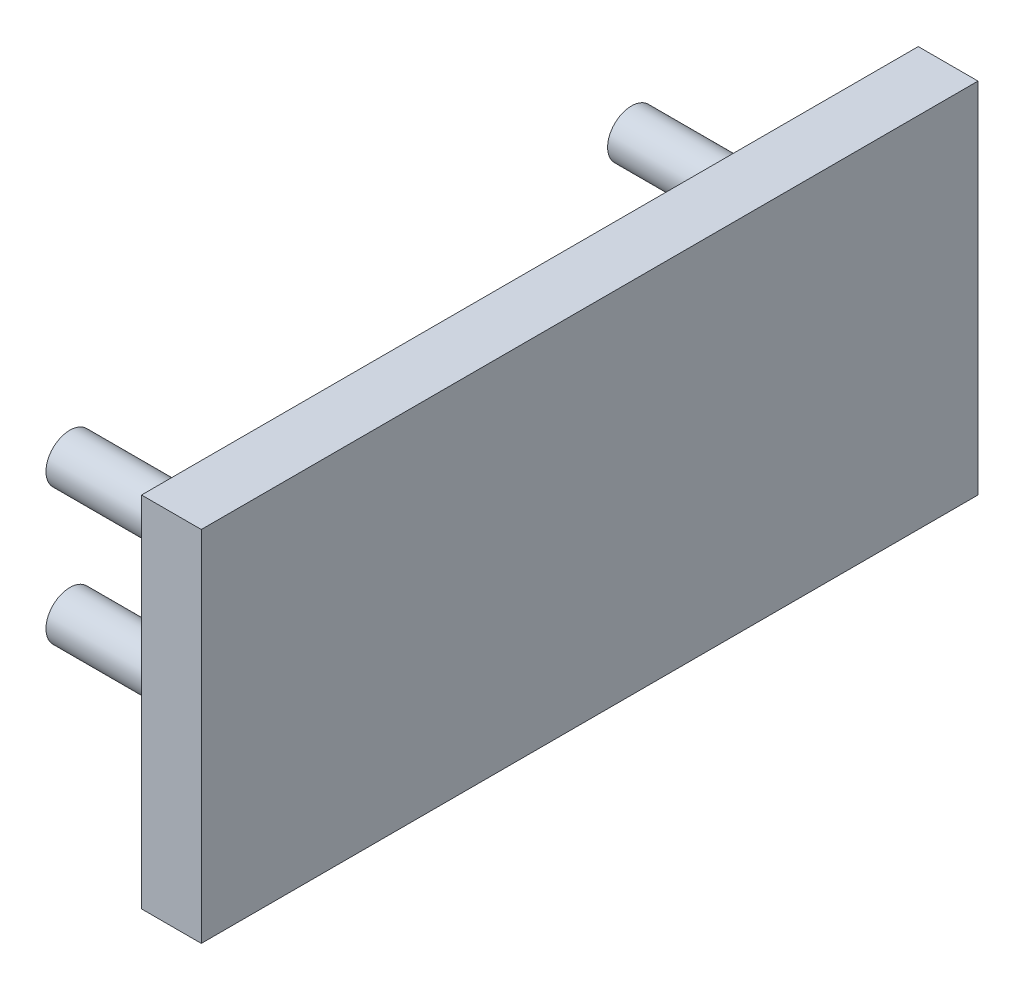
SolidWorks part; units mm, degrees
ref_plane "Front Plane" through (0, 0, 0) normal (1, 0, 0) x (0, 1, 0)
ref_plane "Top Plane" through (0, 0, 0) normal (0, 0, 1) x (0, 1, 0)
ref_plane "Right Plane" through (0, 0, 0) normal (0, 1, 0) x (-1, 0, 0)
sketch "Sketch3" plane through (0, 0, 0) normal (1, 0, 0) x (0, 1, 0)
  line L1 (-15, -32.5) -> (15, -32.5)
  line L2 (-15, -32.5) -> (-15, 32.5)
  line L3 (-15, 32.5) -> (15, 32.5)
  line L4 (15, -32.5) -> (15, 32.5)
  line L5 (-15, -32.5) -> (15, 32.5) construction
  line L6 (-15, 32.5) -> (15, -32.5) construction
  point P0 (0, 0)
extrude "Boss-Extrude1" add sketch "Sketch3" along normal blind 5
sketch "Sketch4" plane through (0, 0, 0) normal (-1, 0, 0) x (0, -1, 0)
  line L1 (-5.7, -23.5) -> (5.7, -23.5) construction
  line L2 (-5.7, -23.5) -> (-5.7, 23.5) construction
  line L3 (-5.7, 23.5) -> (5.7, 23.5) construction
  line L4 (5.7, -23.5) -> (5.7, 23.5) construction
  line L5 (-5.7, -23.5) -> (5.7, 23.5) construction
  line L6 (-5.7, 23.5) -> (5.7, -23.5) construction
  line L7 (2.75, 0) -> (-2.75, 0) construction
  line L8 (0, 2.75) -> (0, -2.75) construction
  circle A0 centre (-5.7, -23.5) radius 2
  circle A1 centre (-5.7, 23.5) radius 2
  circle A2 centre (5.7, -23.5) radius 2
  circle A3 centre (5.7, 23.5) radius 2
  point P0 (0, 0)
extrude "Boss-Extrude2" add sketch "Sketch4" along normal blind 15
